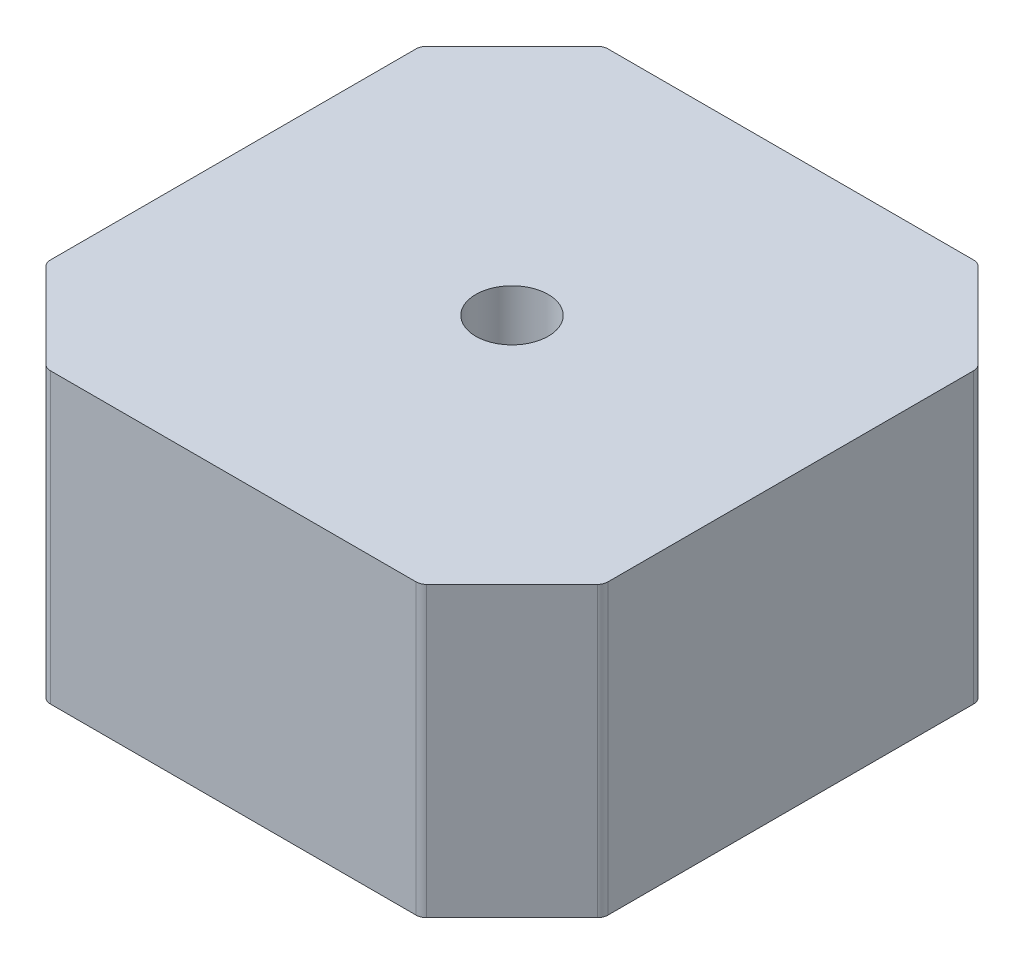
SolidWorks part; units mm, degrees
ref_plane "Front Plane" through (0, 0, 0) normal (0, 0, 1) x (1, 0, 0)
ref_plane "Top Plane" through (0, 0, 0) normal (0, 1, 0) x (1, 0, 0)
ref_plane "Right Plane" through (0, 0, 0) normal (1, 0, 0) x (0, 0, -1)
sketch "Sketch1" plane through (0, 0, 0) normal (0, 1, 0) x (1, 0, 0)
  line L0 (-21.15, 14.2053) -> (-14.2053, 21.15)
  line L1 (-21.15, 21.15) -> (21.15, 21.15)
  line L2 (-21.15, 21.15) -> (-21.15, -21.15)
  line L3 (-21.15, -21.15) -> (21.15, -21.15)
  line L4 (21.15, 21.15) -> (21.15, -21.15)
  line L5 (-21.15, 21.15) -> (21.15, -21.15) construction
  line L6 (-21.15, -21.15) -> (21.15, 21.15) construction
  line L7 (0, -55) -> (0, 55) construction
  line L8 (-23.4996, 17.9721) -> (17.7187, 31.7638) construction
  line L9 (-7.9515, -28.4957) -> (33.2669, -14.704) construction
  line L10 (-12.2477, -4.0981) -> (12.915, 4.3214) construction
  line L11 (-55, 0) -> (55, 0) construction
  line L12 (-21.15, -14.2053) -> (-14.2053, -21.15)
  line L13 (21.15, -14.2053) -> (14.2053, -21.15)
  line L14 (21.15, 14.2053) -> (14.2053, 21.15)
  arc A0 (-13.8704, 21.15) -> (-14.4422, 20.9131) centre (-13.8704, 20.3413) ccw
  arc A1 (-21.15, 13.8704) -> (-20.9131, 14.4422) centre (-20.3413, 13.8704) cw
  arc A2 (-13.8704, -21.15) -> (-14.4422, -20.9131) centre (-13.8704, -20.3413) cw
  arc A3 (-21.15, -13.8704) -> (-20.9131, -14.4422) centre (-20.3413, -13.8704) ccw
  arc A4 (13.8704, -21.15) -> (14.4422, -20.9131) centre (13.8704, -20.3413) ccw
  arc A5 (21.15, -13.8704) -> (20.9131, -14.4422) centre (20.3413, -13.8704) cw
  arc A6 (13.8704, 21.15) -> (14.4422, 20.9131) centre (13.8704, 20.3413) cw
  arc A7 (21.15, 13.8704) -> (20.9131, 14.4422) centre (20.3413, 13.8704) ccw
  point P0 (0, 0)
  dimension "D4" = 0.8087
  dimension "D1" = 42.3
  dimension "D2" = 25
  dimension "D3" = 49
extrude "Boss-Extrude1" add sketch "Sketch1" along normal blind 21.9 contours L4 A7 L14 A6 L1 A0 L0 A1 L2 A3 L12 A2 L3 A4 L13 A5
sketch "Sketch2" plane through (0, 21.9, 0) normal (0, 1, 0) x (1, 0, 0)
  circle A0 centre (0, 0) radius 2.75
  dimension "D1" = 5.5
extrude "Cut-Extrude1" cut sketch "Sketch2" against normal through all both and the other way through all
